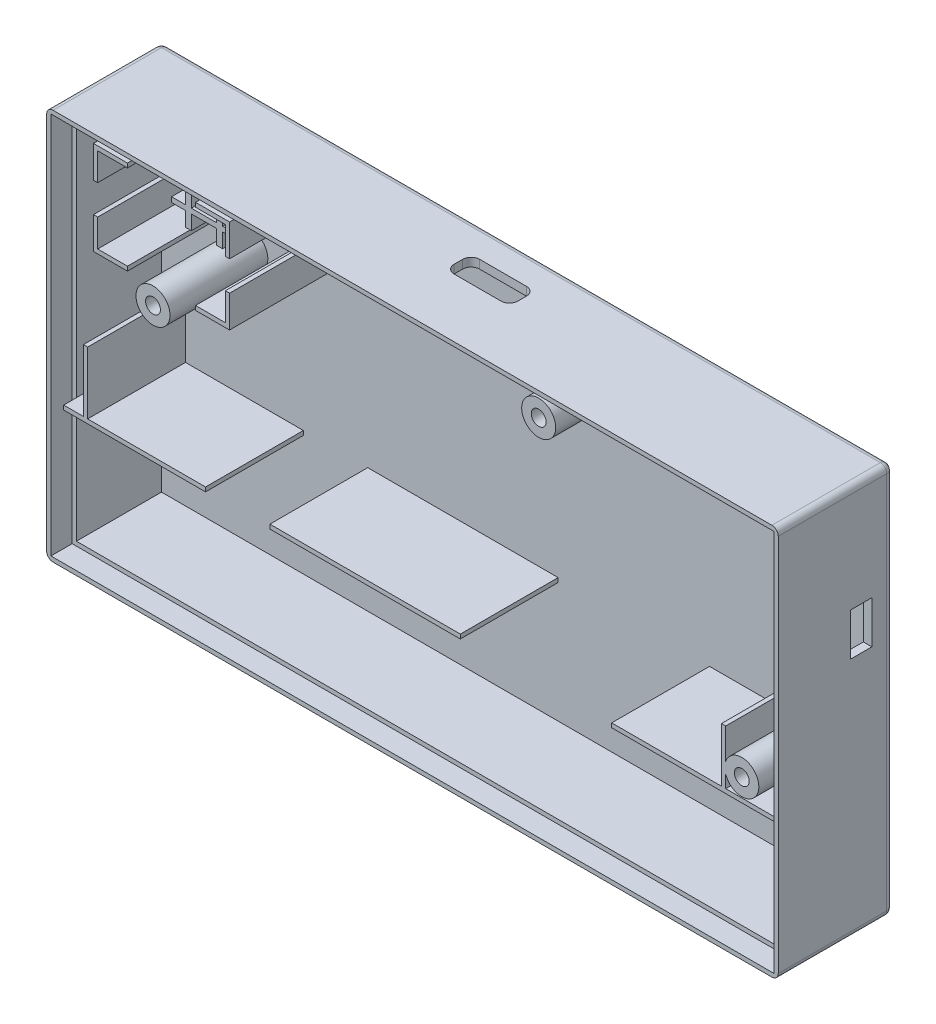
SolidWorks part; units mm, degrees
ref_plane "前视基准面" through (0, 0, 0) normal (0, 0, 1) x (1, 0, 0)
ref_plane "上视基准面" through (0, 0, 0) normal (0, 1, 0) x (1, 0, 0)
ref_plane "右视基准面" through (0, 0, 0) normal (1, 0, 0) x (0, 0, -1)
sketch "草图1" plane through (0, 0, 0) normal (0, 0, 1) x (1, 0, 0)
  line L1 (-82.2853, 34.8182) -> (89.7147, 34.8182)
  line L2 (-82.2853, 34.8182) -> (-82.2853, -57.1818)
  line L3 (-82.2853, -57.1818) -> (89.7147, -57.1818)
  line L4 (89.7147, 34.8182) -> (89.7147, -57.1818)
  dimension "D1" = 172
  dimension "D2" = 92
extrude "凸台-拉伸1" add sketch "草图1" along normal blind 2 contours L2 L1 L4 L3
sketch "草图2" plane through (0, 0, 2) normal (0, 0, 1) x (1, 0, 0)
  line L0 (-82.2853, 34.8182) -> (89.7147, 34.8182) construction
  line L1 (-80.2853, 32.8182) -> (87.7147, 32.8182)
  line L2 (-80.2853, 32.8182) -> (-80.2853, -55.1818)
  line L3 (-80.2853, -55.1818) -> (87.7147, -55.1818)
  line L4 (87.7147, 32.8182) -> (87.7147, -55.1818)
  line L5 (89.7147, 34.8182) -> (89.7147, -57.1818) construction
  line L6 (-82.2853, -57.1818) -> (89.7147, -57.1818) construction
  line L7 (-82.2853, 34.8182) -> (-82.2853, -57.1818) construction
  line M5 (-82.2853, -57.1818) -> (89.7147, -57.1818)
  line M6 (89.7147, -57.1818) -> (89.7147, 34.8182)
  line M7 (89.7147, 34.8182) -> (-82.2853, 34.8182)
  line M8 (-82.2853, 34.8182) -> (-82.2853, -57.1818)
  dimension "D1" = 2
  dimension "D2" = 2
  dimension "D3" = 2
  dimension "D4" = 2
extrude "凸台-拉伸2" add sketch "草图2" along normal blind 25 contours L1 L4 L3 L2 M8 M5 M6 M7
sketch "草图3" plane through (0, 0, 2) normal (0, 0, 1) x (1, 0, 0)
  line L0 (-80.2853, 32.8182) -> (-80.2853, -55.1818) construction
  line L1 (-71.2853, 32.8182) -> (-63.2853, 32.8182)
  line L2 (-71.2853, 32.8182) -> (-71.2853, 25.3182)
  line L3 (-71.2853, 10.8182) -> (-63.2853, 10.8182)
  line L4 (-39.2853, 32.8182) -> (-39.2853, 25.3182)
  line L5 (-80.2853, 32.8182) -> (87.7147, 32.8182) construction
  line L6 (-63.2853, 32.8182) -> (-63.2853, 31.8182)
  line L7 (-70.2853, 31.8182) -> (-63.2853, 31.8182)
  line L8 (-70.2853, 31.8182) -> (-70.2853, 25.3182)
  line L9 (-70.2853, 11.8182) -> (-63.2853, 11.8182)
  line L10 (-40.2853, 31.8182) -> (-40.2853, 25.3182)
  line L11 (-47.2853, 32.8182) -> (-47.2853, 31.8182)
  line L12 (-40.2853, 25.3182) -> (-39.2853, 25.3182)
  line L13 (-40.2853, 18.3182) -> (-39.2853, 18.3182)
  line L14 (-71.2853, 25.3182) -> (-70.2853, 25.3182)
  line L15 (-71.2853, 18.3182) -> (-70.2853, 18.3182)
  line L16 (-63.2853, 10.8182) -> (-63.2853, 11.8182)
  line L17 (-47.2853, 11.8182) -> (-47.2853, 10.8182)
  line L18 (-47.2853, 31.8182) -> (-40.2853, 31.8182)
  line L19 (-47.2853, 32.8182) -> (-39.2853, 32.8182)
  line L20 (-71.2853, 18.3182) -> (-71.2853, 10.8182)
  line L21 (-70.2853, 18.3182) -> (-70.2853, 11.8182)
  line L22 (-47.2853, 11.8182) -> (-40.2853, 11.8182)
  line L23 (-47.2853, 10.8182) -> (-39.2853, 10.8182)
  line L24 (-40.2853, 18.3182) -> (-40.2853, 11.8182)
  line L25 (-39.2853, 18.3182) -> (-39.2853, 10.8182)
  dimension "D1" = 9
  dimension "D2" = 22
  dimension "D3" = 0
  dimension "D4" = 32
  dimension "D5" = 1
  dimension "D6" = 1
  dimension "D7" = 1
  dimension "D8" = 1
  dimension "D9" = 7.5
  dimension "D10" = 7.5
  dimension "D11" = 8
  dimension "D12" = 8
extrude "凸台-拉伸3" add sketch "草图3" along normal blind 25
sketch "草图4" plane through (0, 0, 2) normal (0, 0, 1) x (1, 0, 0)
  line L0 (-59.65, 24.4383) -> (-59.65, 21.142)
  line L1 (-62.9196, 25.5282) -> (-59.65, 25.5282)
  line L2 (-62.9196, 25.5282) -> (-62.9196, 24.4383)
  line L3 (-62.9196, 24.4383) -> (-59.65, 24.4383)
  line L4 (-47.6081, 25.5282) -> (-47.6081, 24.4383)
  line L5 (-62.9196, 21.142) -> (-59.65, 21.142)
  line L6 (-62.9196, 21.142) -> (-62.9196, 19.9724)
  line L7 (-62.9196, 19.9724) -> (-59.65, 19.9724)
  line L8 (-47.6081, 21.142) -> (-47.6081, 19.9724)
  line L9 (-59.65, 28.851) -> (-58.2677, 28.851)
  line L10 (-59.65, 28.851) -> (-59.65, 25.5282)
  line L11 (-59.65, 16.5433) -> (-58.2677, 16.5433)
  line L12 (-58.2677, 28.851) -> (-58.2677, 25.5282)
  line L13 (-52.3398, 28.851) -> (-50.9043, 28.851)
  line L14 (-52.3398, 28.851) -> (-52.3398, 25.5282)
  line L15 (-52.3398, 16.5433) -> (-50.9043, 16.5433)
  line L16 (-50.9043, 28.851) -> (-50.9043, 25.5282)
  line L17 (-58.2677, 24.4383) -> (-58.2677, 21.142)
  line L18 (-58.2677, 25.5282) -> (-52.3398, 25.5282)
  line L19 (-58.2677, 24.4383) -> (-52.3398, 24.4383)
  line L20 (-58.2677, 21.142) -> (-52.3398, 21.142)
  line L21 (-58.2677, 19.9724) -> (-52.3398, 19.9724)
  line L22 (-59.65, 19.9724) -> (-59.65, 16.5433)
  line L23 (-58.2677, 19.9724) -> (-58.2677, 16.5433)
  line L24 (-52.3398, 19.9724) -> (-52.3398, 16.5433)
  line L25 (-50.9043, 21.142) -> (-47.6081, 21.142)
  line L26 (-50.9043, 19.9724) -> (-50.9043, 16.5433)
  line L27 (-50.9043, 19.9724) -> (-47.6081, 19.9724)
  line L28 (-50.9043, 24.4383) -> (-47.6081, 24.4383)
  line L29 (-50.9043, 25.5282) -> (-47.6081, 25.5282)
  line L30 (-52.3398, 24.4383) -> (-52.3398, 21.142)
  line L31 (-50.9043, 24.4383) -> (-50.9043, 21.142)
extrude "凸台-拉伸4" add sketch "草图4" along normal blind 15
sketch "草图5" plane through (0, 0, 2) normal (0, 0, 1) x (1, 0, 0)
  line L0 (-80.2853, 32.8182) -> (-71.2853, 32.8182) construction
  line L1 (-80.2853, 32.8182) -> (-80.2853, -55.1818) construction
  circle A0 centre (-59.2853, 4.8182) radius 4
  dimension "D3" = 8
  dimension "D1" = 28
  dimension "D2" = 21
extrude "凸台-拉伸5" add sketch "草图5" along normal blind 23 contours A0
sketch "草图6" plane through (0, 0, 25) normal (0, 0, 1) x (1, 0, 0)
  circle A0 centre (-59.2853, 4.8182) radius 1.75
  dimension "D1" = 3.5
extrude "切除-拉伸1" cut sketch "草图6" against normal blind 30
sketch "草图7" plane through (0, 0, 0) normal (0, 0, -1) x (-1, 0, 0)
  circle A0 centre (59.2853, 4.8182) radius 3
  dimension "D1" = 6
extrude "切除-拉伸2" cut sketch "草图7" against normal blind 22
sketch "草图8" plane through (0, 0, 2) normal (0, 0, 1) x (1, 0, 0)
  circle A0 centre (31.3927, 27.2972) radius 4
  circle A1 centre (79.1447, -21.9788) radius 4
  circle A2 centre (-59.2853, 4.8182) radius 1.75 construction
  dimension "D1" = 90.678
  dimension "D2" = 22.479
  dimension "D3" = 8
  dimension "D4" = 138.43
  dimension "D5" = 26.797
  dimension "D6" = 8
extrude "凸台-拉伸6" add sketch "草图8" along normal blind 23
sketch "草图9" plane through (0, 0, 25) normal (0, 0, 1) x (1, 0, 0)
  circle A0 centre (31.3927, 27.2972) radius 1.75
  dimension "D1" = 3.5
extrude "切除-拉伸3" cut sketch "草图9" against normal blind 30
sketch "草图10" plane through (0, 0, 25) normal (0, 0, 1) x (1, 0, 0)
  circle A0 centre (79.1447, -21.9788) radius 1.75
  dimension "D1" = 3.5
extrude "切除-拉伸4" cut sketch "草图10" against normal blind 30
sketch "草图11" plane through (0, 0, 0) normal (0, 0, -1) x (-1, 0, 0)
  circle A0 centre (-31.3927, 27.2972) radius 3
  circle A1 centre (-79.1447, -21.9788) radius 3
  dimension "D1" = 6
  dimension "D2" = 6
extrude "切除-拉伸5" cut sketch "草图11" against normal blind 22
sketch "草图12" plane through (0, 0, 2) normal (0, 0, 1) x (1, 0, 0)
  line L0 (87.7147, 32.8182) -> (87.7147, -55.1818) construction
  line L1 (87.7147, -26.2397) -> (75.3673, -26.2397)
  line L2 (87.7147, -26.2397) -> (87.7147, -27.2397)
  line L3 (87.7147, -27.2397) -> (48.5601, -27.2397)
  line L4 (48.5601, -26.2397) -> (48.5601, -27.2397)
  line L5 (-80.2853, 32.8182) -> (-80.2853, -55.1818) construction
  line L6 (-80.2853, -25.9587) -> (-75.6441, -25.9587)
  line L7 (-80.2853, -25.9587) -> (-80.2853, -26.9587)
  line L8 (-80.2853, -26.9587) -> (-46.9292, -26.9587)
  line L9 (-46.9292, -25.9587) -> (-46.9292, -26.9587)
  line L10 (-74.6441, -25.9587) -> (-46.9292, -25.9587)
  line L11 (-31.801, -25.9587) -> (12.9702, -25.9587)
  line L12 (-31.801, -25.9587) -> (-31.801, -26.9587)
  line L13 (-31.801, -26.9587) -> (12.9702, -26.9587)
  line L14 (12.9702, -25.9587) -> (12.9702, -26.9587)
  line L16 (-75.6441, -25.9587) -> (-75.6441, -11.3234)
  line L17 (-75.6441, -11.3234) -> (-74.6441, -11.3234)
  line L18 (-74.6441, -25.9587) -> (-74.6441, -11.3234)
  line L20 (75.3673, -26.2397) -> (75.3673, -13.4688)
  line L21 (75.3673, -13.4688) -> (74.3673, -13.4688)
  line L22 (74.3673, -26.2397) -> (74.3673, -13.4688)
  line L23 (74.3673, -26.2397) -> (48.5601, -26.2397)
  dimension "D1" = 1
  dimension "D2" = 1
  dimension "D3" = 1
extrude "凸台-拉伸7" add sketch "草图12" along normal blind 23
sketch "草图13" plane through (0, 34.8182, 0) normal (0, 1, 0) x (1, 0, 0)
  line L0 (89.7147, -27) -> (-82.2853, -27) construction
  line L1 (-2.2853, -7.2) -> (12.7147, -7.2)
  line L2 (-2.2853, -7.2) -> (-2.2853, -13.2)
  line L3 (-2.2853, -13.2) -> (12.7147, -13.2)
  line L4 (12.7147, -7.2) -> (12.7147, -13.2)
  line L5 (89.7147, -27) -> (89.7147, 0) construction
  dimension "D1" = 13.8
  dimension "D2" = 77
  dimension "D3" = 15
  dimension "D4" = 6
extrude "切除-拉伸6" cut sketch "草图13" against normal blind 23
fillet "圆角1" radius 2 4 edges at (12.7147, 33.8182, 13.2) (12.7147, 33.8182, 7.2) (-2.2853, 33.8182, 13.2) (-2.2853, 33.8182, 7.2)
fillet "圆角2" radius 3 3 edges at (76.1447, -21.9788, 0) (28.3927, 27.2972, 0) (-62.2853, 4.8182, 0)
sketch "草图14" plane through (89.7147, 0, 0) normal (1, 0, 0) x (0, 0, -1)
  line L0 (-27, -57.1818) -> (-27, 34.8182) construction
  line L1 (-10, 9.8182) -> (-5, 9.8182)
  line L2 (-10, 9.8182) -> (-10, -0.1818)
  line L3 (-10, -0.1818) -> (-5, -0.1818)
  line L4 (-5, 9.8182) -> (-5, -0.1818)
  line L5 (-27, 34.8182) -> (0, 34.8182) construction
  dimension "D1" = 17
  dimension "D2" = 25
  dimension "D3" = 10
  dimension "D4" = 5
extrude "切除-拉伸7" cut sketch "草图14" against normal blind 23
sketch "草图15" plane through (0, 0, 27) normal (0, 0, 1) x (1, 0, 0)
  line L0 (89.7147, 34.8182) -> (-82.2853, 34.8182) construction
  line L1 (-81.2853, 33.8182) -> (88.7147, 33.8182)
  line L2 (-81.2853, 33.8182) -> (-81.2853, -56.1818)
  line L3 (-81.2853, -56.1818) -> (88.7147, -56.1818)
  line L4 (88.7147, 33.8182) -> (88.7147, -56.1818)
  line L5 (-82.2853, 34.8182) -> (-82.2853, -57.1818) construction
  line L6 (-82.2853, -57.1818) -> (89.7147, -57.1818) construction
  line L7 (89.7147, -57.1818) -> (89.7147, 34.8182) construction
  line L8 (-71.2853, 32.8182) -> (-39.2853, 32.8182)
  line M9 (-80.2853, 32.8182) -> (-71.2853, 32.8182)
  line M15 (-63.2853, 32.8182) -> (-47.2853, 32.8182)
  line M21 (-39.2853, 32.8182) -> (87.7147, 32.8182)
  line M22 (87.7147, 32.8182) -> (87.7147, -55.1818)
  line M23 (87.7147, -55.1818) -> (-80.2853, -55.1818)
  line M24 (-80.2853, -55.1818) -> (-80.2853, 32.8182)
  dimension "D1" = 1
  dimension "D2" = 1
  dimension "D3" = 1
  dimension "D4" = 1
extrude "切除-拉伸8" cut sketch "草图15" against normal blind 5 contours L4 L1 L2 L3 L8 M9 M15 M21 M22 M23 M24
fillet "圆角3" radius 1.5 8 edges at (89.7147, -11.1818, 0) (3.7147, 34.8182, 0) (-82.2853, -11.1818, 0) (3.7147, -57.1818, 0) (89.7147, -57.1818, 13.5) (89.7147, 34.8182, 13.5) (-82.2853, 34.8182, 13.5) (-82.2853, -57.1818, 13.5)
